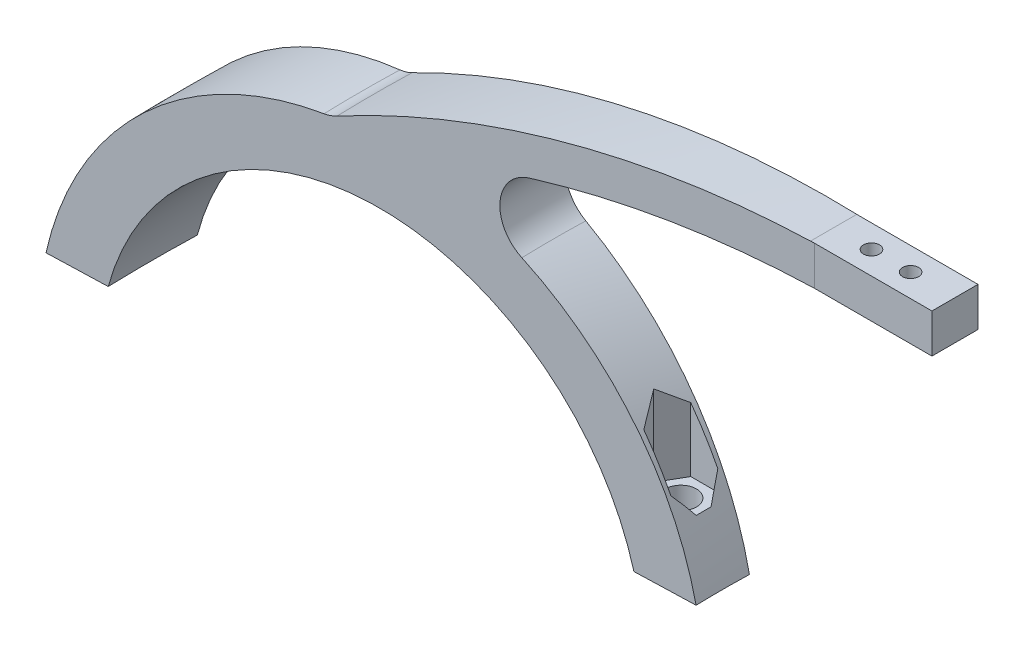
SolidWorks part; units mm, degrees
ref_plane "前视基准面" through (0, 0, 0) normal (0, 0, 1) x (1, 0, 0)
ref_plane "上视基准面" through (0, 0, 0) normal (0, 1, 0) x (1, 0, 0)
ref_plane "右视基准面" through (0, 0, 0) normal (1, 0, 0) x (0, 0, -1)
sketch "草图1" plane through (0, 0, 0) normal (0, 0, 1) x (1, 0, 0)
  line L2 (0, 67.5) -> (0, 9.6189) construction
  line L3 (-10, 101.8917) -> (-10, 81.8917) construction
  line L4 (10, 101.8917) -> (10, 81.8917) construction
  line L5 (-10, 101.8917) -> (-10, 111.8917) construction
  line L6 (-10, 111.8917) -> (110, 111.8917) construction
  line L7 (110, 111.8917) -> (110, 101.8917)
  line L8 (110, 101.8917) -> (10, 101.8917) construction
  line L9 (297.5, 163.1376) -> (297.5, -27.4228) construction
  line L10 (-80.6226, 17.5) -> (-65.192, 17.5)
  line L11 (80.6226, 17.5) -> (65.192, 17.5)
  line L12 (110, -143.1083) -> (110, -158.1083) construction
  arc A0 (80.6226, 17.5) -> (10, 81.8917) centre (0, 0) ccw
  arc A1 (65.192, 17.5) -> (-65.192, 17.5) centre (0, 0) ccw
  arc A2 (-10, 81.8917) -> (-80.6226, 17.5) centre (0, 0) ccw
  arc A3 (110, 111.8917) -> (-10, 81.8917) centre (110, -143.1083) ccw
  arc A4 (110, 101.8917) -> (10, 81.8917) centre (110, -158.1083) ccw
  arc A5 (-10, 81.8917) -> (-80.6226, 17.5) centre (8.0509, -8.8299) ccw construction
  dimension "D1" = 82.5
  dimension "D2" = 67.5
  dimension "D3" = 20
  dimension "D4" = 20
  dimension "D5" = 120
  dimension "D6" = 10
  dimension "D7" = 297.5
  dimension "D8" = 50
revolve "旋转3" add sketch "草图1" angle 1.8 about L9
sketch "草图9" plane through (0, 17.5, 0) normal (0, -1, 0) x (1, 0, 0)
  line L0 (55, 0) -> (-55, 0) construction
  circle A0 centre (-70, 0) radius 4
  circle A1 centre (70, 0) radius 4
  circle A3 centre (0, 0) radius 70 construction
  point P11 (-68.9184, -12.2577)
  dimension "D2" = 8
  dimension "D1" = 140
extrude "切除-拉伸1" cut sketch "草图9" against normal up to next
fillet "圆角3" radius 10 2 edges at (10, 81.8917, 0) (-10, 81.8917, 0)
ref_plane "基准面1" through (110.0925, 0, 0) normal (-1, 0, 0) x (0, 0, 1)
sketch "草图12" plane through (110.0925, 0, 0) normal (-1, 0, 0) x (0, 0, 1)
  line L4 (-5.8895, 111.8917) -> (-5.8895, 101.8917)
  line L5 (5.8895, 111.8917) -> (-5.8895, 111.8917)
  line L6 (5.8895, 101.8917) -> (5.8895, 111.8917)
  line L7 (-5.8895, 101.8917) -> (5.8895, 101.8917)
  line L8 (-5.8895, 111.8917) -> (-5.8895, 101.8917)
  line L9 (5.8895, 111.8917) -> (-5.8895, 111.8917)
  line L10 (5.8895, 101.8917) -> (5.8895, 111.8917)
  line L11 (-5.8895, 101.8917) -> (5.8895, 101.8917)
  dimension "D1" = 0
extrude "凸台-拉伸1" add sketch "草图12" against normal blind 30 and the other way blind 1 separate body
sketch "草图14" plane through (0, 0, 0) normal (0, 0, 1) x (1, 0, 0)
  circle A0 centre (0, 0) radius 92.5 construction
  dimension "D1" = 185
sketch "草图15" plane through (0, 111.8917, 0) normal (0, 1, 0) x (1, 0, 0)
  circle A1 centre (128.75, 0) radius 2.05
  circle A4 centre (118.75, 0) radius 2.05
extrude "切除-拉伸3" cut sketch "草图15" against normal blind 20
sketch "草图16" plane through (0, 17.5, 0) normal (0, -1, 0) x (1, 0, 0)
  line L1 (-63.0718, 0) -> (-66.5359, 6)
  line L2 (-66.5359, 6) -> (-73.4641, 6)
  line L3 (-73.4641, 6) -> (-76.9282, 0)
  line L4 (-76.9282, 0) -> (-73.4641, -6)
  line L5 (-73.4641, -6) -> (-66.5359, -6)
  line L6 (-66.5359, -6) -> (-63.0718, 0)
  line L7 (76.9282, 0) -> (73.4641, 6)
  line L8 (73.4641, 6) -> (66.5359, 6)
  line L9 (66.5359, 6) -> (63.0718, 0)
  line L10 (63.0718, 0) -> (66.5359, -6)
  line L11 (66.5359, -6) -> (73.4641, -6)
  line L12 (73.4641, -6) -> (76.9282, 0)
  circle A0 centre (-70, 0) radius 6 construction
  circle A1 centre (70, 0) radius 6 construction
  dimension "D1" = 12
  dimension "D2" = 12
extrude "切除-拉伸4" cut sketch "草图16" against normal blind 25 from offset 15 offset against normal yes
sketch "草图17" plane through (0, 0, 0) normal (0, 0, 1) x (1, 0, 0)
  circle A0 centre (0, 0) radius 67.6135 construction
